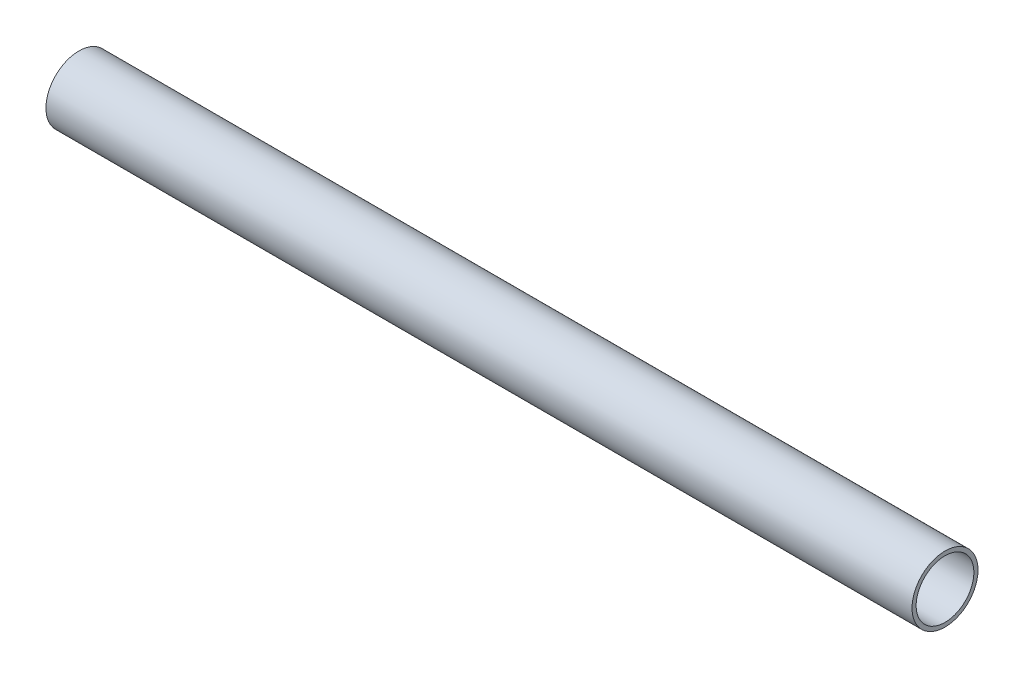
SolidWorks part; units mm, degrees
ref_plane "Ön Düzlem" through (0, 0, 0) normal (0, 0, 1) x (1, 0, 0)
ref_plane "Üst Düzlem" through (0, 0, 0) normal (0, 1, 0) x (1, 0, 0)
ref_plane "Sağ Düzlem" through (0, 0, 0) normal (1, 0, 0) x (0, 0, -1)
sketch "Çizim1" plane through (0, 0, 0) normal (1, 0, 0) x (0, 0, -1)
  circle A0 centre (0, 0) radius 7
  circle A1 centre (0, 0) radius 8
  dimension "D1" = 16
  dimension "D2" = 14
extrude "Yükseklik-Ekstrüzyon1" add sketch "Çizim1" along normal blind 210
